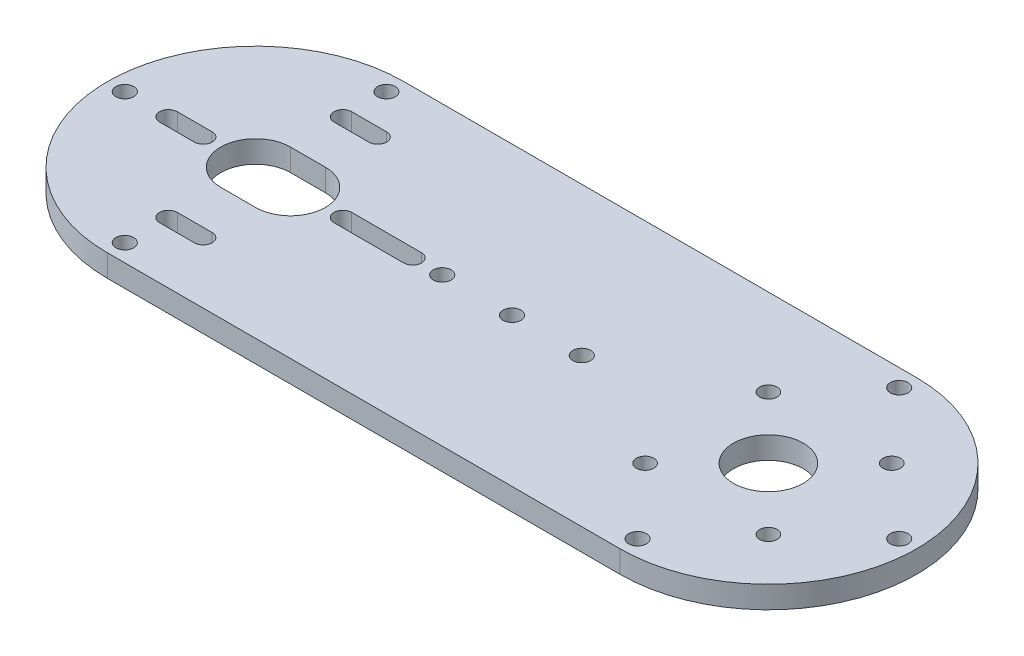
SolidWorks part; units mm, degrees
ref_plane "Front Plane" through (0, 0, 0) normal (0, 0, 1) x (1, 0, 0)
ref_plane "Top Plane" through (0, 0, 0) normal (0, 1, 0) x (1, 0, 0)
ref_plane "Right Plane" through (0, 0, 0) normal (1, 0, 0) x (0, 0, -1)
sketch "Sketch1" plane through (0, 0, 0) normal (0, 1, 0) x (1, 0, 0)
  line L0 (-147, 0) -> (0, 0) construction
  line L1 (-147, 42.5) -> (0, 42.5)
  line L6 (-147, -42.5) -> (0, -42.5)
  line L7 (-147, 0) -> (-137, 0) construction
  line L10 (-147, 10) -> (-137, 10)
  line L13 (-147, -10) -> (-137, -10)
  line L16 (-147, 25) -> (-137, 25) construction
  line L19 (17.6777, -17.6777) -> (-17.6777, 17.6777) construction
  line L20 (-147, 27.55) -> (-137, 27.55)
  line L21 (-17.6777, -17.6777) -> (17.6777, 17.6777) construction
  line L24 (-147, 22.45) -> (-137, 22.45)
  line L29 (-147, -25) -> (-137, -25) construction
  line L30 (-147, -22.45) -> (-137, -22.45)
  line L31 (-147, -27.55) -> (-137, -27.55)
  line L32 (-122, 0) -> (-102, 0) construction
  line L33 (-122, 2.55) -> (-102, 2.55)
  line L34 (-122, -2.55) -> (-102, -2.55)
  line L35 (-172, 0) -> (-162, 0) construction
  line L36 (-172, 2.55) -> (-162, 2.55)
  line L37 (-172, -2.55) -> (-162, -2.55)
  line L39 (0, 0) -> (-142, 0) construction
  line L40 (0, 0) -> (0, -89.6752) construction
  line L41 (0, -89.6752) -> (-142, -89.6752) construction
  line L42 (-142, 0) -> (-142, -89.6752) construction
  circle A1 centre (-147, 0) radius 10 construction
  circle A4 centre (-147, 0) radius 14.2875 construction
  circle A5 centre (0, 0) radius 10
  circle A8 centre (-147, 0) radius 37.5 construction
  circle A13 centre (-147, 0) radius 42.5
  circle A14 centre (0, 0) radius 42.5
  circle A15 centre (0, 0) radius 37.5 construction
  circle A16 centre (0, 37.5) radius 2.55
  circle A17 centre (37.5, 0) radius 2.55
  circle A18 centre (0, -37.5) radius 2.55
  circle A19 centre (-37.5, 0) radius 2.55 construction
  circle A29 centre (0, 0) radius 25 construction
  circle A30 centre (-17.6777, 17.6777) radius 2.5
  circle A31 centre (17.6777, -17.6777) radius 2.5
  circle A32 centre (-17.6777, -17.6777) radius 2.5
  circle A33 centre (17.6777, 17.6777) radius 2.5
  circle A38 centre (-184.5, 0) radius 2.55
  circle A39 centre (-147, 37.5) radius 2.55
  circle A40 centre (-147, -37.5) radius 2.55
  circle A41 centre (-109.5, 0) radius 2.55 construction
  arc A42 (-147, 10) -> (-147, -10) centre (-147, 0) ccw
  arc A43 (-137, -10) -> (-137, 10) centre (-137, 0) ccw
  circle A44 centre (-147, 0) radius 25 construction
  arc A45 (-147, 27.55) -> (-147, 22.45) centre (-147, 25) ccw
  arc A46 (-137, 22.45) -> (-137, 27.55) centre (-137, 25) ccw
  arc A47 (-147, -22.45) -> (-147, -27.55) centre (-147, -25) ccw
  arc A48 (-137, -27.55) -> (-137, -22.45) centre (-137, -25) ccw
  arc A49 (-122, 2.55) -> (-122, -2.55) centre (-122, 0) ccw
  arc A50 (-102, -2.55) -> (-102, 2.55) centre (-102, 0) ccw
  arc A51 (-172, 2.55) -> (-172, -2.55) centre (-172, 0) ccw
  arc A52 (-162, -2.55) -> (-162, 2.55) centre (-162, 0) ccw
  circle A53 centre (-73.5, 0) radius 2.55
  circle A54 centre (-93.5, 0) radius 2.55
  circle A55 centre (-53.5, 0) radius 2.55
  point P31 (-142, 0)
  point P41 (-142, 25)
  point P46 (-142, -25)
  point P62 (-112, 0)
  point P77 (-167, 0)
  dimension "D2" = 20
  dimension "D4" = 5.1
  dimension "D5" = 45
  dimension "D6" = 28.575
  dimension "D7" = 20
  dimension "D9" = 142
  dimension "D10" = 85
  dimension "D8" = 75
  dimension "D11" = 5.1
  dimension "D12" = 75
  dimension "D13" = 50
  dimension "D14" = 50
  dimension "D15" = 5
  dimension "D16" = 10
  dimension "D18" = 20
  dimension "D19" = 5.1
  dimension "D20" = 10
  dimension "D22" = 5.1
  dimension "D3" = 147
  dimension "D17" = 5.1
  dimension "D21" = 20
  dimension "D23" = 20
  dimension "D24" = 20
extrude "Boss-Extrude1" add sketch "Sketch1" against normal blind 6.35
